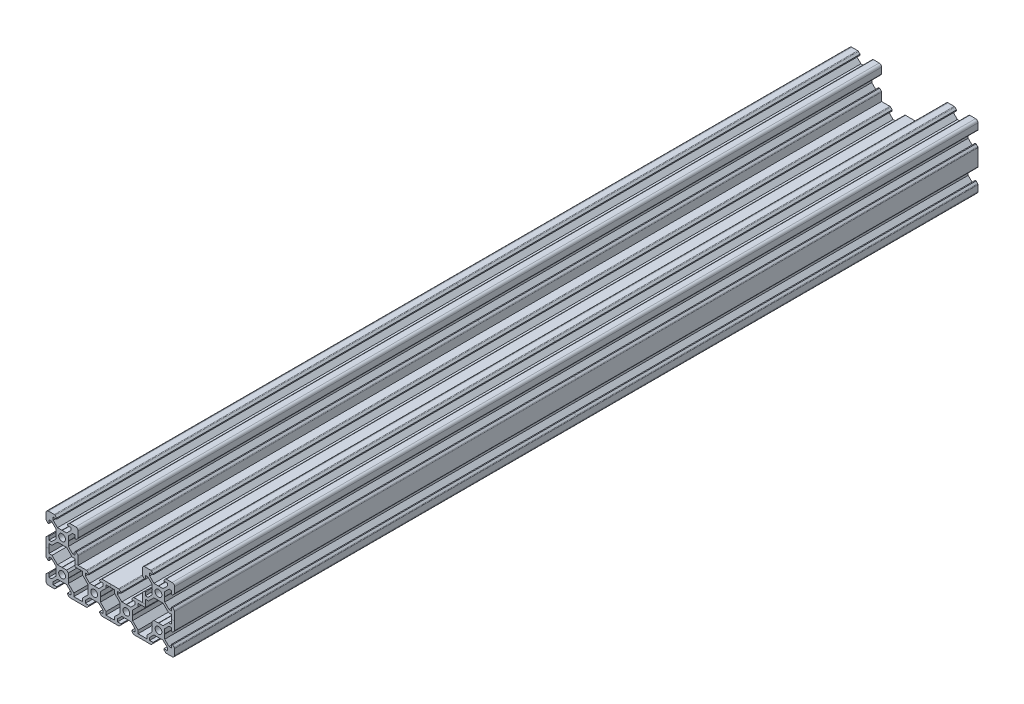
SolidWorks part; units mm, degrees
material "6063-T5"
ref_plane "Front" through (0, 0, 0) normal (0, 0, 1) x (1, 0, 0)
ref_plane "Top" through (0, 0, 0) normal (0, 1, 0) x (1, 0, 0)
ref_plane "Right" through (0, 0, 0) normal (1, 0, 0) x (0, 0, -1)
sketch "Sketch1" plane through (0, 0, 0) normal (0, 0, 1) x (1, 0, 0)
  line L0 (0, 32.3219) -> (0, -50.1713) construction
  line L1 (-2.8395, 3.9) -> (-0.1, 3.9)
  line L2 (-3.9, 2.8395) -> (-3.9, 0.1)
  line L3 (-2.8395, -3.9) -> (-0.1, -3.9)
  line L4 (3.9, 2.8395) -> (3.9, 0.1)
  line L5 (-29.7903, 0) -> (30, 0) construction
  line L6 (-0.1, -3.9) -> (0, -3.8)
  line L7 (-8.5, 10) -> (-4.8658, 10)
  line L8 (-10, 8.5) -> (-10, 4.8627)
  line L9 (-2.8395, -16.1) -> (-6.24, -12.6995)
  line L10 (10, 8.5) -> (10, 4.8627)
  line L11 (0, -3.8) -> (0.1, -3.9)
  line L12 (0.1, -3.9) -> (2.8395, -3.9)
  line L13 (-0.1, 3.9) -> (0, 3.8)
  line L14 (0, 3.8) -> (0.1, 3.9)
  line L15 (10, -10) -> (-10, 10) construction
  line L16 (-10, -10) -> (10, 10) construction
  line L17 (0.1, 3.9) -> (2.8395, 3.9)
  line L18 (-3.9, 0.1) -> (-3.8, 0)
  line L19 (-3.8, 0) -> (-3.9, -0.1)
  line L20 (-3.9, -0.1) -> (-3.9, -2.8395)
  line L21 (3.9, 0.1) -> (3.8, 0)
  line L22 (3.8, 0) -> (3.9, -0.1)
  line L23 (3.9, -0.1) -> (3.9, -2.8395)
  line L24 (0, -20) -> (58.4732, -20) construction
  line L25 (-3.9, 2.8395) -> (-6.561, 5.5005)
  line L26 (30, -50.1713) -> (30, 32.3219) construction
  line L27 (-5.5005, 8.2) -> (-3.3865, 8.2)
  line L28 (-8.2, 5.5005) -> (-8.2, 3.3865)
  line L29 (-10, -10) -> (-53.8942, -10) construction
  line L30 (8.2, 5.5005) -> (8.2, 3.3865)
  line L31 (-6.561, 5.5005) -> (-8.2, 5.5005)
  line L32 (-2.8395, 3.9) -> (-5.5005, 6.561)
  line L33 (-5.5005, 6.561) -> (-5.5005, 8.2)
  line L34 (6.561, 5.5005) -> (8.2, 5.5005)
  line L35 (3.9, 2.8395) -> (6.561, 5.5005)
  line L36 (5.5005, 6.561) -> (5.5005, 8.2)
  line L37 (2.8395, 3.9) -> (5.5005, 6.561)
  line L38 (6.561, -5.5005) -> (8.2, -5.5005)
  line L39 (-8.2, -12.6995) -> (-8.2, -7.3005)
  line L40 (2.8395, -3.9) -> (5.5005, -6.561)
  line L41 (3.9, -2.8395) -> (6.561, -5.5005)
  line L42 (-6.24, -12.6995) -> (-8.2, -12.6995)
  line L43 (-2.8395, -3.9) -> (-5.5005, -6.561)
  line L44 (-6.561, -5.5005) -> (-8.2, -5.5005)
  line L45 (-3.9, -2.8395) -> (-6.561, -5.5005)
  line L46 (30, -10) -> (10, -10) construction
  line L47 (-8.5, 10) -> (-10, 8.5) construction
  line L48 (8.5, 10) -> (10, 8.5) construction
  line L49 (-10, -10) -> (10, -30) construction
  line L50 (-5.5005, -6.561) -> (-6.24, -7.3005)
  line L51 (-3.9, -19.9) -> (-3.9, -17.1605)
  line L52 (-3.9, -17.1605) -> (-6.561, -14.4995)
  line L53 (10, 32.3219) -> (10, -50.1713) construction
  line L54 (-10, -30) -> (10, -10) construction
  line L55 (-4.3771, 9.7976) -> (-3.3865, 8.807)
  line L56 (-3.3865, 8.807) -> (-3.3865, 8.2)
  line L57 (4.3771, 9.7976) -> (3.3865, 8.807)
  line L58 (3.3865, 8.807) -> (3.3865, 8.2)
  line L59 (4.8658, 10) -> (8.5, 10)
  line L60 (3.3865, 8.2) -> (5.5005, 8.2)
  line L61 (-9.7968, 4.3732) -> (-8.807, 3.3865)
  line L62 (-8.807, 3.3865) -> (-8.2, 3.3865)
  line L63 (-9.7976, -4.3802) -> (-8.807, -3.3865)
  line L64 (-8.807, -3.3865) -> (-8.2, -3.3865)
  line L65 (9.7968, 4.3732) -> (8.807, 3.3865)
  line L66 (8.807, 3.3865) -> (8.2, 3.3865)
  line L67 (8.807, -3.3865) -> (8.2, -3.3865)
  line L68 (9.7976, -4.3802) -> (8.807, -3.3865)
  line L69 (-10, -4.87) -> (-10, -15.13)
  line L70 (-8.2, -3.3865) -> (-8.2, -5.5005)
  line L71 (10, -4.87) -> (10, -10)
  line L72 (8.2, -3.3865) -> (8.2, -5.5005)
  line L73 (-6.561, -14.4995) -> (-8.2, -14.4995)
  line L74 (-8.2, -16.6135) -> (-8.2, -14.4995)
  line L75 (-8.807, -16.6135) -> (-8.2, -16.6135)
  line L76 (-9.7976, -15.6198) -> (-8.807, -16.6135)
  line L77 (-10, -28.5) -> (-10, -24.8627)
  line L78 (-9.7968, -24.3732) -> (-8.807, -23.3865)
  line L79 (-8.807, -23.3865) -> (-8.2, -23.3865)
  line L80 (-8.2, -25.5005) -> (-8.2, -23.3865)
  line L81 (-6.561, -25.5005) -> (-8.2, -25.5005)
  line L82 (-3.9, -22.8395) -> (-6.561, -25.5005)
  line L83 (-3.9, -22.8395) -> (-3.9, -20.1)
  line L84 (-3.9, -20.1) -> (-3.8, -20)
  line L85 (-3.8, -20) -> (-3.9, -19.9)
  line L86 (0, -23.8) -> (0.1, -23.9)
  line L87 (-0.1, -23.9) -> (0, -23.8)
  line L88 (-2.8395, -23.9) -> (-0.1, -23.9)
  line L89 (0.1, -23.9) -> (2.8395, -23.9)
  line L90 (-2.8395, -23.9) -> (-5.5005, -26.561)
  line L91 (-5.5005, -28.2) -> (-3.3865, -28.2)
  line L92 (-5.5005, -26.561) -> (-5.5005, -28.2)
  line L93 (-4.3771, -29.7976) -> (-3.3865, -28.807)
  line L94 (-3.3865, -28.807) -> (-3.3865, -28.2)
  line L95 (-4.8658, -30) -> (-8.5, -30)
  line L96 (5.5005, -26.561) -> (5.5005, -28.2)
  line L97 (2.8395, -23.9) -> (5.5005, -26.561)
  line L98 (4.3771, -29.7976) -> (3.3865, -28.807)
  line L99 (3.3865, -28.807) -> (3.3865, -28.2)
  line L100 (3.3865, -28.2) -> (5.5005, -28.2)
  line L101 (4.8658, -30) -> (10, -30)
  line L102 (0.1, -16.1) -> (2.8395, -16.1)
  line L103 (0, -16.2) -> (0.1, -16.1)
  line L104 (-0.1, -16.1) -> (0, -16.2)
  line L105 (-2.8395, -16.1) -> (-0.1, -16.1)
  line L106 (3.9, -22.8395) -> (3.9, -20.1)
  line L107 (3.9, -20.1) -> (3.8, -20)
  line L108 (3.8, -20) -> (3.9, -19.9)
  line L109 (3.9, -19.9) -> (3.9, -17.1605)
  line L110 (3.9, -17.1605) -> (2.8395, -16.1)
  line L111 (-6.24, -7.3005) -> (-8.2, -7.3005)
  line L112 (6.24, -7.3005) -> (8.2, -7.3005)
  line L113 (5.5005, -6.561) -> (6.24, -7.3005)
  line L114 (12.6995, -28.2) -> (7.3005, -28.2)
  line L115 (7.3005, -28.2) -> (7.3005, -26.24)
  line L116 (7.3005, -26.24) -> (3.9, -22.8395)
  line L117 (16.1, -19.9) -> (16.1, -17.1605)
  line L118 (16.2, -20) -> (16.1, -19.9)
  line L119 (16.1, -20.1) -> (16.2, -20)
  line L120 (16.1, -22.8395) -> (16.1, -20.1)
  line L121 (20, -16.2) -> (19.9, -16.1)
  line L122 (20.1, -16.1) -> (20, -16.2)
  line L123 (22.8395, -16.1) -> (20.1, -16.1)
  line L124 (19.9, -16.1) -> (17.1605, -16.1)
  line L125 (23.9, -19.9) -> (23.9, -17.1605)
  line L126 (23.8, -20) -> (23.9, -19.9)
  line L127 (23.9, -20.1) -> (23.8, -20)
  line L128 (23.9, -22.8395) -> (23.9, -20.1)
  line L129 (20.1, -23.9) -> (20, -23.8)
  line L130 (22.8395, -23.9) -> (20.1, -23.9)
  line L131 (20, -23.8) -> (19.9, -23.9)
  line L132 (19.9, -23.9) -> (17.1605, -23.9)
  line L133 (12.6995, -28.2) -> (12.6995, -26.24)
  line L134 (14.4995, -26.561) -> (14.4995, -28.2)
  line L135 (17.1605, -23.9) -> (14.4995, -26.561)
  line L136 (12.6995, -26.24) -> (16.1, -22.8395)
  line L137 (16.6135, -28.807) -> (16.6135, -28.2)
  line L138 (16.6135, -28.2) -> (14.4995, -28.2)
  line L139 (15.6229, -29.7976) -> (16.6135, -28.807)
  line L140 (15.1342, -30) -> (10, -30)
  line L141 (20, 32.3219) -> (20, -50.1713) construction
  line L142 (10, -10) -> (30, -30) construction
  line L143 (30, -10) -> (10, -30) construction
  line L144 (27.3005, -28.2) -> (27.3005, -26.24)
  line L145 (25.5005, -26.561) -> (25.5005, -28.2)
  line L146 (24.3771, -29.7976) -> (23.3865, -28.807)
  line L147 (23.3865, -28.807) -> (23.3865, -28.2)
  line L148 (23.3865, -28.2) -> (25.5005, -28.2)
  line L149 (24.8658, -30) -> (30, -30)
  line L150 (27.3005, -28.2) -> (32.6995, -28.2)
  line L151 (25.5005, -26.561) -> (22.8395, -23.9)
  line L152 (27.3005, -26.24) -> (23.9, -22.8395)
  line L153 (25.5005, -13.439) -> (25.5005, -11.8)
  line L154 (27.3005, -11.8) -> (27.3005, -13.76)
  line L155 (27.3005, -13.76) -> (23.9, -17.1605)
  line L156 (25.5005, -13.439) -> (22.8395, -16.1)
  line L157 (12.6995, -11.8) -> (12.6995, -13.76)
  line L158 (14.4995, -13.439) -> (14.4995, -11.8)
  line L159 (17.1605, -16.1) -> (14.4995, -13.439)
  line L160 (16.1, -17.1605) -> (12.6995, -13.76)
  line L161 (23.3865, -11.193) -> (23.3865, -11.8)
  line L162 (16.6135, -11.193) -> (16.6135, -11.8)
  line L163 (16.6135, -11.8) -> (14.4995, -11.8)
  line L164 (23.3865, -11.8) -> (25.5005, -11.8)
  line L165 (15.6229, -10.2024) -> (16.6135, -11.193)
  line L166 (24.3771, -10.2024) -> (23.3865, -11.193)
  line L167 (24.8658, -10) -> (30, -10)
  line L168 (27.3005, -11.8) -> (32.6995, -11.8)
  line L169 (15.1342, -10) -> (10, -10)
  line L170 (12.6995, -11.8) -> (8.2, -11.8)
  line L171 (8.2, -11.8) -> (8.2, -7.3005)
  line L172 (60, -3.8) -> (59.9, -3.9)
  line L173 (60.1, -3.9) -> (60, -3.8)
  line L174 (63.8, 0) -> (63.9, -0.1)
  line L175 (63.9, 0.1) -> (63.8, 0)
  line L176 (56.1, 0.1) -> (56.2, 0)
  line L177 (56.2, 0) -> (56.1, -0.1)
  line L178 (60.1, 3.9) -> (60, 3.8)
  line L179 (60, 3.8) -> (59.9, 3.9)
  line L180 (62.8395, 3.9) -> (60.1, 3.9)
  line L181 (59.9, 3.9) -> (57.1605, 3.9)
  line L182 (63.9, 2.8395) -> (63.9, 0.1)
  line L183 (63.9, -0.1) -> (63.9, -2.8395)
  line L184 (62.8395, -3.9) -> (60.1, -3.9)
  line L185 (59.9, -3.9) -> (57.1605, -3.9)
  line L186 (56.1, -0.1) -> (56.1, -2.8395)
  line L187 (56.1, 2.8395) -> (56.1, 0.1)
  line L188 (60, -23.8) -> (59.9, -23.9)
  line L189 (60.1, -23.9) -> (60, -23.8)
  line L190 (60, -16.2) -> (59.9, -16.1)
  line L191 (60.1, -16.1) -> (60, -16.2)
  line L192 (63.8, -20) -> (63.9, -19.9)
  line L193 (63.9, -20.1) -> (63.8, -20)
  line L194 (56.2, -20) -> (56.1, -19.9)
  line L195 (56.1, -20.1) -> (56.2, -20)
  line L196 (40, -16.2) -> (40.1, -16.1)
  line L197 (39.9, -16.1) -> (40, -16.2)
  line L198 (36.2, -20) -> (36.1, -19.9)
  line L199 (36.1, -20.1) -> (36.2, -20)
  line L200 (43.8, -20) -> (43.9, -19.9)
  line L201 (43.9, -20.1) -> (43.8, -20)
  line L202 (40, -23.8) -> (40.1, -23.9)
  line L203 (39.9, -23.9) -> (40, -23.8)
  line L204 (56.1, -22.8395) -> (56.1, -20.1)
  line L205 (59.9, -23.9) -> (57.1605, -23.9)
  line L206 (62.8395, -23.9) -> (60.1, -23.9)
  line L207 (63.9, -22.8395) -> (63.9, -20.1)
  line L208 (63.9, -19.9) -> (63.9, -17.1605)
  line L209 (62.8395, -16.1) -> (60.1, -16.1)
  line L210 (59.9, -16.1) -> (57.1605, -16.1)
  line L211 (56.1, -19.9) -> (56.1, -17.1605)
  line L212 (43.9, -19.9) -> (43.9, -17.1605)
  line L213 (43.9, -22.8395) -> (43.9, -20.1)
  line L214 (40.1, -23.9) -> (42.8395, -23.9)
  line L215 (37.1605, -23.9) -> (39.9, -23.9)
  line L216 (36.1, -22.8395) -> (36.1, -20.1)
  line L217 (36.1, -19.9) -> (36.1, -17.1605)
  line L218 (37.1605, -16.1) -> (39.9, -16.1)
  line L219 (40.1, -16.1) -> (42.8395, -16.1)
  line L220 (42.8395, -23.9) -> (45.5005, -26.561)
  line L221 (47.3005, -26.24) -> (43.9, -22.8395)
  line L222 (43.9, -17.1605) -> (47.3005, -13.76)
  line L223 (42.8395, -16.1) -> (45.5005, -13.439)
  line L224 (34.4995, -13.439) -> (37.1605, -16.1)
  line L225 (32.6995, -13.76) -> (36.1, -17.1605)
  line L226 (34.4995, -26.561) -> (37.1605, -23.9)
  line L227 (32.6995, -26.24) -> (36.1, -22.8395)
  line L228 (47.3005, -11.8) -> (47.3005, -13.76)
  line L229 (45.5005, -13.439) -> (45.5005, -11.8)
  line L230 (47.3005, -28.2) -> (47.3005, -26.24)
  line L231 (45.5005, -26.561) -> (45.5005, -28.2)
  line L232 (34.4995, -26.561) -> (34.4995, -28.2)
  line L233 (32.6995, -28.2) -> (32.6995, -26.24)
  line L234 (34.4995, -13.439) -> (34.4995, -11.8)
  line L235 (32.6995, -11.8) -> (32.6995, -13.76)
  line L236 (43.3865, -28.2) -> (45.5005, -28.2)
  line L237 (43.3865, -28.807) -> (43.3865, -28.2)
  line L238 (44.3771, -29.7976) -> (43.3865, -28.807)
  line L239 (35.6229, -29.7976) -> (36.6135, -28.807)
  line L240 (36.6135, -28.807) -> (36.6135, -28.2)
  line L241 (36.6135, -28.2) -> (34.4995, -28.2)
  line L242 (44.3771, -10.2024) -> (43.3865, -11.193)
  line L243 (43.3865, -11.193) -> (43.3865, -11.8)
  line L244 (43.3865, -11.8) -> (45.5005, -11.8)
  line L245 (35.6229, -10.2024) -> (36.6135, -11.193)
  line L246 (36.6135, -11.193) -> (36.6135, -11.8)
  line L247 (36.6135, -11.8) -> (34.4995, -11.8)
  line L248 (35.1342, -30) -> (30, -30)
  line L249 (35.1342, -10) -> (30, -10)
  line L250 (51.8, -3.3865) -> (51.8, -5.5005)
  line L251 (51.193, -3.3865) -> (51.8, -3.3865)
  line L252 (50.2024, -4.3802) -> (51.193, -3.3865)
  line L253 (51.8, -11.8) -> (51.8, -7.3005)
  line L254 (50, -4.87) -> (50, -10)
  line L255 (44.8658, -10) -> (50, -10)
  line L256 (47.3005, -11.8) -> (51.8, -11.8)
  line L257 (62.8395, -16.1) -> (66.24, -12.6995)
  line L258 (63.9, -17.1605) -> (66.561, -14.4995)
  line L259 (63.9, -22.8395) -> (66.561, -25.5005)
  line L260 (62.8395, -23.9) -> (65.5005, -26.561)
  line L261 (57.1605, -23.9) -> (54.4995, -26.561)
  line L262 (52.6995, -26.24) -> (56.1, -22.8395)
  line L263 (63.9, 2.8395) -> (66.561, 5.5005)
  line L264 (62.8395, 3.9) -> (65.5005, 6.561)
  line L265 (57.1605, 3.9) -> (54.4995, 6.561)
  line L266 (56.1, 2.8395) -> (53.439, 5.5005)
  line L267 (63.9, -2.8395) -> (66.561, -5.5005)
  line L268 (62.8395, -3.9) -> (65.5005, -6.561)
  line L269 (57.1605, -3.9) -> (54.4995, -6.561)
  line L270 (56.1, -2.8395) -> (53.439, -5.5005)
  line L271 (64.3771, -29.7976) -> (63.3865, -28.807)
  line L272 (64.8658, -30) -> (68.5, -30)
  line L273 (65.5005, -28.2) -> (63.3865, -28.2)
  line L274 (55.6229, -29.7976) -> (56.6135, -28.807)
  line L275 (56.6135, -28.2) -> (54.4995, -28.2)
  line L276 (56.6135, -28.807) -> (56.6135, -28.2)
  line L277 (55.1342, -30) -> (50, -30)
  line L278 (44.8658, -30) -> (50, -30)
  line L279 (44.3771, -29.7976) -> (43.3865, -28.807)
  line L280 (43.3865, -28.807) -> (43.3865, -28.2)
  line L281 (43.3865, -28.2) -> (45.5005, -28.2)
  line L282 (47.3005, -28.2) -> (52.6995, -28.2)
  line L283 (70, -28.5) -> (70, -24.8627)
  line L284 (65.5005, -26.561) -> (65.5005, -28.2)
  line L285 (54.4995, -26.561) -> (54.4995, -28.2)
  line L286 (52.6995, -28.2) -> (52.6995, -26.24)
  line L287 (47.3005, -28.2) -> (47.3005, -26.24)
  line L288 (45.5005, -26.561) -> (45.5005, -28.2)
  line L289 (66.561, -5.5005) -> (68.2, -5.5005)
  line L290 (66.24, -7.3005) -> (68.2, -7.3005)
  line L291 (69.7976, -4.3802) -> (68.807, -3.3865)
  line L292 (68.807, -3.3865) -> (68.2, -3.3865)
  line L293 (68.2, -3.3865) -> (68.2, -5.5005)
  line L294 (68.2, -12.6995) -> (68.2, -7.3005)
  line L295 (70, -4.87) -> (70, -15.13)
  line L296 (69.7976, -15.6198) -> (68.807, -16.6135)
  line L297 (68.807, -16.6135) -> (68.2, -16.6135)
  line L298 (68.2, -16.6135) -> (68.2, -14.4995)
  line L299 (66.561, -14.4995) -> (68.2, -14.4995)
  line L300 (66.24, -12.6995) -> (68.2, -12.6995)
  line L301 (56.1, -17.1605) -> (57.1605, -16.1)
  line L302 (66.561, -25.5005) -> (68.2, -25.5005)
  line L303 (68.2, -25.5005) -> (68.2, -23.3865)
  line L304 (68.807, -23.3865) -> (68.2, -23.3865)
  line L305 (69.7968, -24.3732) -> (68.807, -23.3865)
  line L306 (53.76, -7.3005) -> (51.8, -7.3005)
  line L307 (53.439, -5.5005) -> (51.8, -5.5005)
  line L308 (54.4995, -6.561) -> (53.76, -7.3005)
  line L309 (65.5005, -6.561) -> (66.24, -7.3005)
  line L310 (54.4995, 6.561) -> (54.4995, 8.2)
  line L311 (56.6135, 8.2) -> (54.4995, 8.2)
  line L312 (56.6135, 8.807) -> (56.6135, 8.2)
  line L313 (55.6229, 9.7976) -> (56.6135, 8.807)
  line L314 (55.1342, 10) -> (51.5, 10)
  line L315 (50, 8.5) -> (50, 4.8627)
  line L316 (50.2032, 4.3732) -> (51.193, 3.3865)
  line L317 (51.193, 3.3865) -> (51.8, 3.3865)
  line L318 (51.8, 5.5005) -> (51.8, 3.3865)
  line L319 (53.439, 5.5005) -> (51.8, 5.5005)
  line L320 (66.561, 5.5005) -> (68.2, 5.5005)
  line L321 (68.2, 5.5005) -> (68.2, 3.3865)
  line L322 (68.807, 3.3865) -> (68.2, 3.3865)
  line L323 (69.7968, 4.3732) -> (68.807, 3.3865)
  line L324 (70, 8.5) -> (70, 4.8627)
  line L325 (68.5, 10) -> (64.8658, 10)
  line L326 (64.3771, 9.7976) -> (63.3865, 8.807)
  line L327 (63.3865, 8.807) -> (63.3865, 8.2)
  line L328 (65.5005, 8.2) -> (63.3865, 8.2)
  line L329 (65.5005, 6.561) -> (65.5005, 8.2)
  line L330 (63.3865, -28.807) -> (63.3865, -28.2)
  circle A0 centre (0, 0) radius 2.1
  circle A1 centre (0, -20) radius 2.1
  circle A2 centre (20, -20) radius 2.1
  circle A3 centre (60, 0) radius 2.1
  circle A4 centre (60, -20) radius 2.1
  circle A5 centre (40, -20) radius 2.1
  arc A6 (-8.5, 10) -> (-10, 8.5) centre (-8.5, 8.5) ccw
  arc A7 (10, 8.5) -> (8.5, 10) centre (8.5, 8.5) ccw
  arc A8 (-4.3771, 9.7976) -> (-4.8658, 10) centre (-4.8658, 9.3088) ccw
  arc A9 (4.3771, 9.7976) -> (4.8658, 10) centre (4.8658, 9.3088) cw
  arc A10 (-10, 4.8627) -> (-9.7968, 4.3732) centre (-9.3088, 4.8627) ccw
  arc A11 (9.7968, 4.3732) -> (10, 4.8627) centre (9.3088, 4.8627) ccw
  arc A12 (10, -4.87) -> (9.7976, -4.3802) centre (9.3062, -4.87) ccw
  arc A13 (-9.7976, -4.3802) -> (-10, -4.87) centre (-9.3062, -4.87) ccw
  arc A14 (-9.7976, -15.6198) -> (-10, -15.13) centre (-9.3062, -15.13) cw
  arc A15 (-8.5, -30) -> (-10, -28.5) centre (-8.5, -28.5) cw
  arc A16 (-10, -24.8627) -> (-9.7968, -24.3732) centre (-9.3088, -24.8627) cw
  arc A17 (-4.3771, -29.7976) -> (-4.8658, -30) centre (-4.8658, -29.3088) cw
  arc A18 (4.3771, -29.7976) -> (4.8658, -30) centre (4.8658, -29.3088) ccw
  arc A19 (15.6229, -29.7976) -> (15.1342, -30) centre (15.1342, -29.3088) cw
  arc A20 (24.3771, -29.7976) -> (24.8658, -30) centre (24.8658, -29.3088) ccw
  arc A21 (15.6229, -10.2024) -> (15.1342, -10) centre (15.1342, -10.6912) ccw
  arc A22 (24.3771, -10.2024) -> (24.8658, -10) centre (24.8658, -10.6912) cw
  arc A23 (44.3771, -29.7976) -> (44.8658, -30) centre (44.8658, -29.3088) ccw
  arc A24 (35.6229, -29.7976) -> (35.1342, -30) centre (35.1342, -29.3088) cw
  arc A25 (44.3771, -10.2024) -> (44.8658, -10) centre (44.8658, -10.6912) cw
  arc A26 (35.6229, -10.2024) -> (35.1342, -10) centre (35.1342, -10.6912) ccw
  arc A27 (50, -4.87) -> (50.2024, -4.3802) centre (50.6938, -4.87) cw
  arc A28 (64.3771, -29.7976) -> (64.8658, -30) centre (64.8658, -29.3088) ccw
  arc A29 (68.5, -30) -> (70, -28.5) centre (68.5, -28.5) ccw
  arc A30 (55.6229, -29.7976) -> (55.1342, -30) centre (55.1342, -29.3088) cw
  arc A31 (44.3771, -29.7976) -> (44.8658, -30) centre (44.8658, -29.3088) ccw
  arc A32 (69.7976, -4.3802) -> (70, -4.87) centre (69.3062, -4.87) cw
  arc A33 (69.7976, -15.6198) -> (70, -15.13) centre (69.3062, -15.13) ccw
  arc A34 (70, -24.8627) -> (69.7968, -24.3732) centre (69.3088, -24.8627) ccw
  arc A35 (55.6229, 9.7976) -> (55.1342, 10) centre (55.1342, 9.3088) ccw
  arc A36 (50, 8.5) -> (51.5, 10) centre (51.5, 8.5) cw
  arc A37 (50.2032, 4.3732) -> (50, 4.8627) centre (50.6912, 4.8627) cw
  arc A38 (70, 4.8627) -> (69.7968, 4.3732) centre (69.3088, 4.8627) cw
  arc A39 (68.5, 10) -> (70, 8.5) centre (68.5, 8.5) cw
  arc A40 (64.3771, 9.7976) -> (64.8658, 10) centre (64.8658, 9.3088) cw
  point P23 (-9.25, 9.25)
  point P69 (9.25, 9.25)
  point P188 (10, -28.2)
  point P223 (30, -28.2)
  point P320 (30, -11.8)
  dimension "D1" = 4.2
  dimension "D16" = 1.5
  dimension "D21" = 0.529
  dimension "D25" = 0.53
  dimension "D27" = 90
  dimension "D2" = 0.1
  dimension "D3" = 0.1
  dimension "D4" = 7.8
  dimension "D5" = 7.8
  dimension "D6" = 20
  dimension "D7" = 20
  dimension "D8" = 20
  dimension "D9" = 10
  dimension "D10" = 0.1
  dimension "D11" = 1.8
  dimension "D12" = 1.8
  dimension "D13" = 5.679
  dimension "D14" = 5.679
  dimension "D15" = 1.639
  dimension "D17" = 90
  dimension "D18" = 6.773
  dimension "D19" = 0.607
  dimension "D20" = 11.001
  dimension "D22" = 0.607
  dimension "D23" = 90
  dimension "D24" = 6.773
  dimension "D26" = 0.53
  dimension "D28" = 0.53
  dimension "D29" = 0.53
  dimension "D30" = 1.8
extrude "Boss-Extrude1" add sketch "Sketch1" along normal blind 500 contours A40 L326 L327 L328 L329 L264 L180 L178 L179 L181 L265 L310 L311 L312 L313 A35 L314 A36 L315 A37 L316 L317 L318 L319 L266 L187 L176 L177 L186 L270 L307 L250 L251 L252 A27 L254 L255 A25 L242 L243 L244 L229 L223 L219 L196 L197 L218 L224 L234 L247 L246
sketch "Sketch2" plane through (0, 0, 500) normal (0, 0, 1) x (1, 0, 0)
  line L0 (-10, -10) -> (70, -10)
  line L1 (-10, -4.87) -> (-10, -15.13) construction
  line L2 (70, -4.87) -> (70, -15.13) construction
split line "TopFixture1 - SplitLine"
sketch "Sketch3" plane through (0, 0, 0) normal (0, 0, -1) x (-1, 0, 0)
  line L0 (-70, -10) -> (10, -10)
  line L1 (-70, -4.87) -> (-70, -15.13) construction
  line L2 (10, -4.87) -> (10, -15.13) construction
split line "TopFixture2 - SplitLine"
sketch "Sketch6" plane through (0, 10, 0) normal (0, 1, 0) x (1, 0, 0)
  line L0 (-8.5, -250) -> (68.5, -250)
  line L1 (-8.5, -500) -> (-8.5, 0) construction
  line L2 (68.5, -500) -> (68.5, 0) construction
split line "TopFixture3 - SplitLine"
sketch "Sketch7" plane through (0, 0, 500) normal (0, 0, 1) x (1, 0, 0)
  line L0 (30, -30) -> (30, -10)
  line L1 (24.8658, -30) -> (35.1342, -30) construction
  line L2 (35.1342, -10) -> (24.8658, -10) construction
split line "SideFixture1 - SplitLine"
sketch "Sketch8" plane through (0, 0, 0) normal (0, 0, -1) x (-1, 0, 0)
  line L0 (-30, -10) -> (-30, -30)
  line L1 (-35.1342, -10) -> (-24.8658, -10) construction
  line L2 (-24.8658, -30) -> (-35.1342, -30) construction
split line "SideFixture2 - SplitLine"
sketch "Sketch9" plane through (-10, 0, 0) normal (-1, 0, 0) x (0, 0, 1)
  line L0 (250, -28.5) -> (250, 8.5)
  line L3 (500, -28.5) -> (0, -28.5) construction
  line L4 (500, 8.5) -> (0, 8.5) construction
split line "SideFixture3 - SplitLine"
equation "\"base-xwidth\" = 500mm"
equation "\"D1@Boss-Extrude1\"=\"base-xwidth\""
